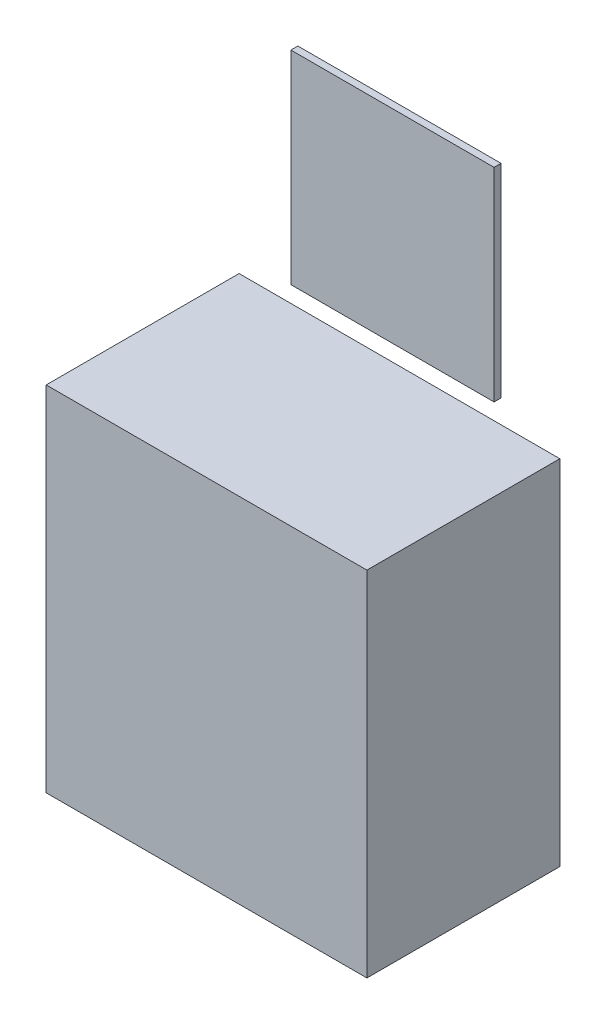
SolidWorks part; units mm, degrees
ref_plane "Front Plane" through (0, 0, 0) normal (0, 0, 1) x (1, 0, 0)
ref_plane "Top Plane" through (0, 0, 0) normal (0, 1, 0) x (1, 0, 0)
ref_plane "Right Plane" through (0, 0, 0) normal (1, 0, 0) x (0, 0, -1)
sketch "Sketch2" plane through (0, 0, 0) normal (0, 0, 1) x (1, 0, 0)
  line L0 (23.2626, 532.4408) -> (-1276.7374, 532.4408)
  line L1 (-666.7374, 782.4408) -> (713.2626, 782.4408)
  line L2 (-666.7374, 782.4408) -> (-666.7374, -737.5592)
  line L3 (-666.7374, -737.5592) -> (713.2626, -737.5592)
  line L4 (713.2626, 782.4408) -> (713.2626, -737.5592)
  line L5 (-766.7374, 882.4408) -> (813.2626, 882.4408)
  line L6 (-766.7374, 882.4408) -> (-766.7374, -837.5592)
  line L7 (-766.7374, -837.5592) -> (813.2626, -837.5592)
  line L8 (813.2626, 882.4408) -> (813.2626, -837.5592)
  line L9 (-1276.7374, 532.4408) -> (1323.2626, 532.4408)
  line L10 (23.2626, 1832.4408) -> (-926.7374, 882.4408)
  line L11 (-926.7374, 882.4408) -> (973.2626, 882.4408)
  line L12 (973.2626, 882.4408) -> (23.2626, 1832.4408)
  line L14 (520.278, 882.4408) -> (-590.1646, 882.4408)
  line L15 (-413.8893, 882.4408) -> (460.4144, 882.4408)
  line L16 (-413.8893, 882.4408) -> (-413.8893, 1756.7358)
  line L17 (-413.8893, 1756.7358) -> (460.4144, 1756.7358)
  line L18 (460.4144, 882.4408) -> (460.4144, 1756.7358)
  circle A0 centre (23.2626, 532.4408) radius 100
  circle A1 centre (23.2626, 532.4408) radius 1300
  point P20 (0, 0)
  point P23 (0, 0)
  point P24 (0, 0)
  dimension "D9" = 2600
  dimension "D12" = 200
  dimension "D1" = 1380
  dimension "D2" = 1520
  dimension "D3" = 100
  dimension "D4" = 100
  dimension "D5" = 100
  dimension "D6" = 100
  dimension "D7" = 250
  dimension "D8" = 690
  dimension "D11" = 45
  dimension "D14" = 874.295
  dimension "D15" = 874.3037
sketch "Sketch3" plane through (0, 0, 0) normal (0, 0, 1) x (1, 0, 0)
  line L0 (23.2626, 532.4408) -> (-1276.7374, 532.4408)
  line L1 (-666.7374, 782.4408) -> (713.2626, 782.4408)
  line L2 (-666.7374, 782.4408) -> (-666.7374, -737.5592)
  line L3 (-666.7374, -737.5592) -> (713.2626, -737.5592)
  line L4 (713.2626, 782.4408) -> (713.2626, -737.5592)
  line L5 (-766.7374, 882.4408) -> (813.2626, 882.4408)
  line L6 (-766.7374, 882.4408) -> (-766.7374, -837.5592)
  line L7 (-766.7374, -837.5592) -> (813.2626, -837.5592)
  line L8 (813.2626, 882.4408) -> (813.2626, -837.5592)
  line L9 (-1276.7374, 532.4408) -> (1323.2626, 532.4408)
  line L10 (23.2626, 1832.4408) -> (-926.7374, 882.4408)
  line L11 (-926.7374, 882.4408) -> (973.2626, 882.4408)
  line L12 (973.2626, 882.4408) -> (23.2626, 1832.4408)
  line L14 (520.278, 882.4408) -> (-590.1646, 882.4408)
  line L15 (-413.8893, 882.4408) -> (460.4144, 882.4408)
  line L16 (-413.8893, 882.4408) -> (-413.8893, 1756.7358)
  line L17 (-413.8893, 1756.7358) -> (460.4144, 1756.7358)
  line L18 (460.4144, 882.4408) -> (460.4144, 1756.7358)
  circle A0 centre (23.2626, 532.4408) radius 100
  circle A1 centre (23.2626, 532.4408) radius 1300
  point P20 (0, 0)
  point P23 (0, 0)
  point P24 (0, 0)
  dimension "D9" = 2600
  dimension "D12" = 200
  dimension "D1" = 1380
  dimension "D2" = 1520
  dimension "D3" = 100
  dimension "D4" = 100
  dimension "D5" = 100
  dimension "D6" = 100
  dimension "D7" = 250
  dimension "D8" = 690
  dimension "D11" = 45
  dimension "D14" = 874.295
  dimension "D15" = 874.3037
extrude "Boss-Extrude3" add sketch "Sketch2" along normal blind 830 contours L2 L3 L4 L1
extrude "Boss-Extrude6" add sketch "Sketch3" along normal blind 30 separate body contours L16 L17 L18 L15
